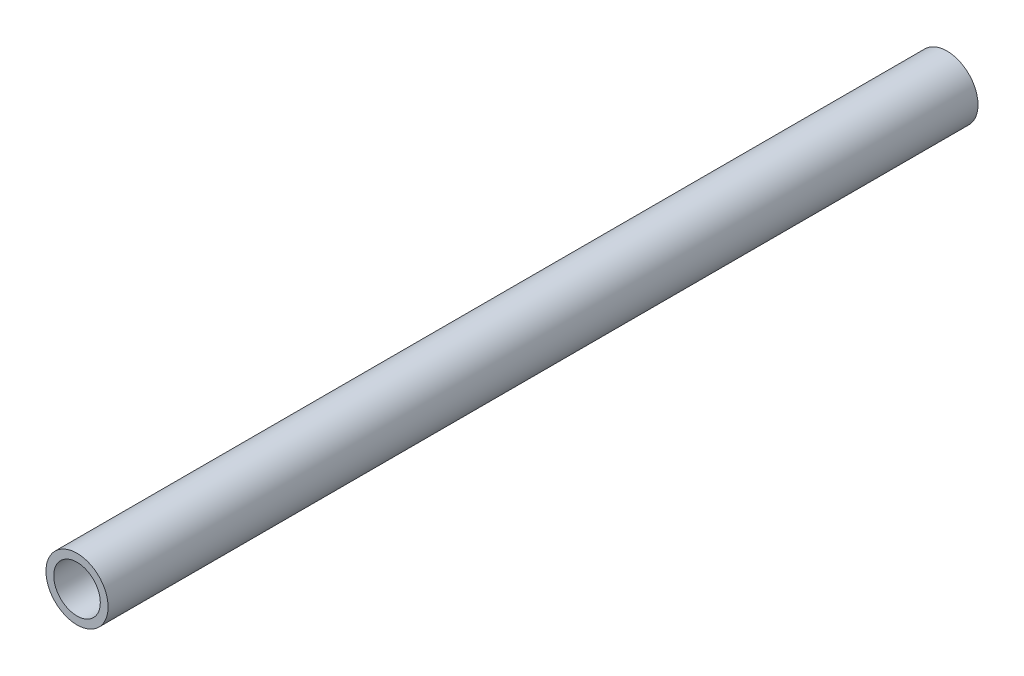
SolidWorks part; units mm, degrees
material "6061-T6 (SS)"
ref_plane "Front Plane" through (0, 0, 0) normal (0, 0, 1) x (1, 0, 0)
ref_plane "Top Plane" through (0, 0, 0) normal (0, 1, 0) x (1, 0, 0)
ref_plane "Right Plane" through (0, 0, 0) normal (1, 0, 0) x (0, 0, -1)
sketch "Sketch1" plane through (0, 0, 0) normal (0, 0, 1) x (1, 0, 0)
  circle A0 centre (0, 0) radius 9.525
  circle A1 centre (0, 0) radius 12.7
  dimension "D1" = 25.4
  dimension "D2" = 3.175
extrude "Boss-Extrude1" add sketch "Sketch1" against normal blind 355.6
